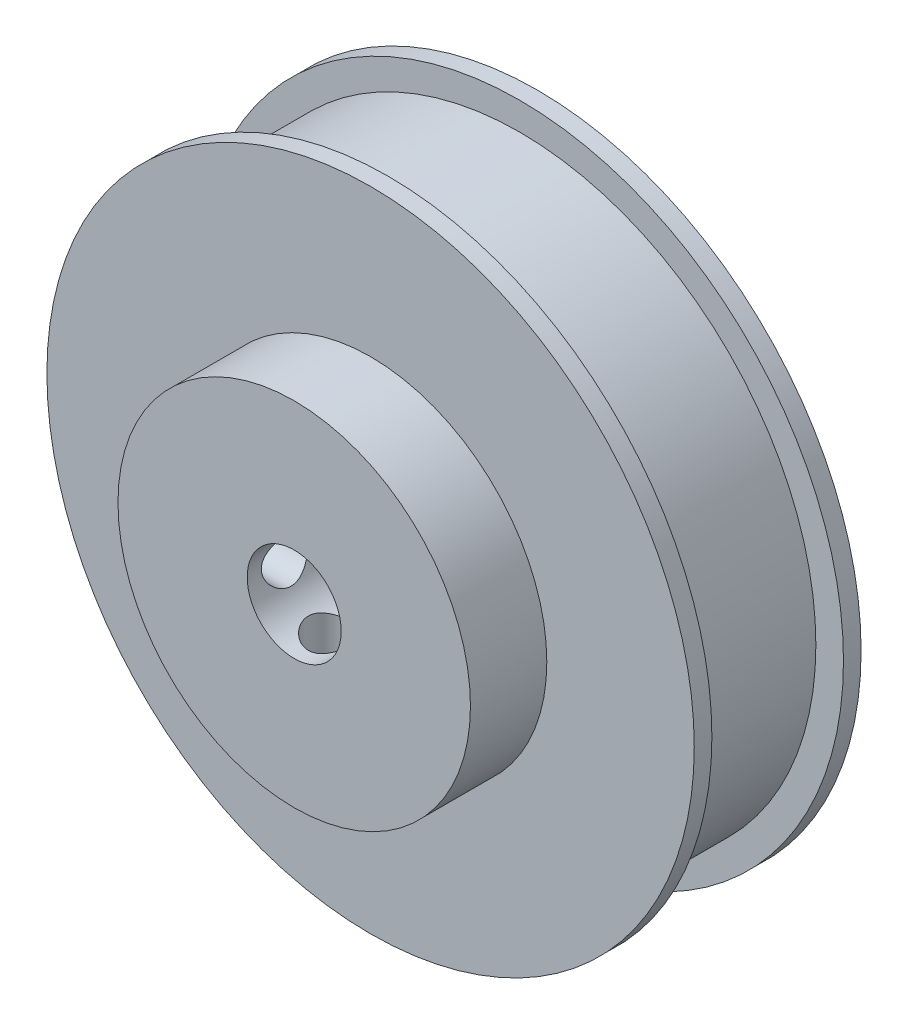
SolidWorks part; units mm, degrees
ref_plane "Alzado" through (0, 0, 0) normal (0, 0, 1) x (1, 0, 0)
ref_plane "Planta" through (0, 0, 0) normal (0, 1, 0) x (1, 0, 0)
ref_plane "Vista lateral" through (0, 0, 0) normal (1, 0, 0) x (0, 0, -1)
sketch "Croquis1" plane through (0, 0, 0) normal (0, 0, 1) x (1, 0, 0)
  circle A0 centre (0, 0) radius 27.55
  dimension "D1" = 55.1
extrude "Saliente-Extruir1" add sketch "Croquis1" along normal blind 1.5
sketch "Croquis2" plane through (0, 0, 1.5) normal (0, 0, 1) x (1, 0, 0)
  circle A0 centre (0, 0) radius 25.2
  dimension "D1" = 50.4
extrude "Saliente-Extruir2" add sketch "Croquis2" along normal blind 11.2
sketch "Croquis3" plane through (0, 0, 12.7) normal (0, 0, 1) x (1, 0, 0)
  circle A0 centre (0, 0) radius 27.55
  dimension "D1" = 55.1
extrude "Saliente-Extruir3" add sketch "Croquis3" along normal blind 1.5
sketch "Croquis8" plane through (0, 0, 14.2) normal (0, 0, 1) x (1, 0, 0)
  circle A0 centre (0, 0) radius 15
  dimension "D1" = 30
extrude "Saliente-Extruir5" add sketch "Croquis8" along normal blind 6.5
sketch "Croquis6" plane through (0, 0, 0) normal (0, 1, 0) x (1, 0, 0)
  line L0 (0, 0) -> (0, -17.5) construction
  circle A0 centre (0, -17.5) radius 2
  dimension "D2" = 4
  dimension "D1" = 17.5
extrude "Cortar-Extruir3" cut sketch "Croquis6" against normal through all
sketch "Croquis5" plane through (0, 0, 0) normal (1, 0, 0) x (0, 0, -1)
  line L0 (0, 0) -> (-17.5, 0) construction
  circle A0 centre (-17.5, 0) radius 2
  dimension "D2" = 4
  dimension "D1" = 17.5
extrude "Cortar-Extruir2" cut sketch "Croquis5" against normal through all
sketch "Croquis4" plane through (0, 0, 20.7) normal (0, 0, 1) x (1, 0, 0)
  circle A0 centre (0, 0) radius 4
  dimension "D1" = 8
extrude "Cortar-Extruir1" cut sketch "Croquis4" against normal through all
